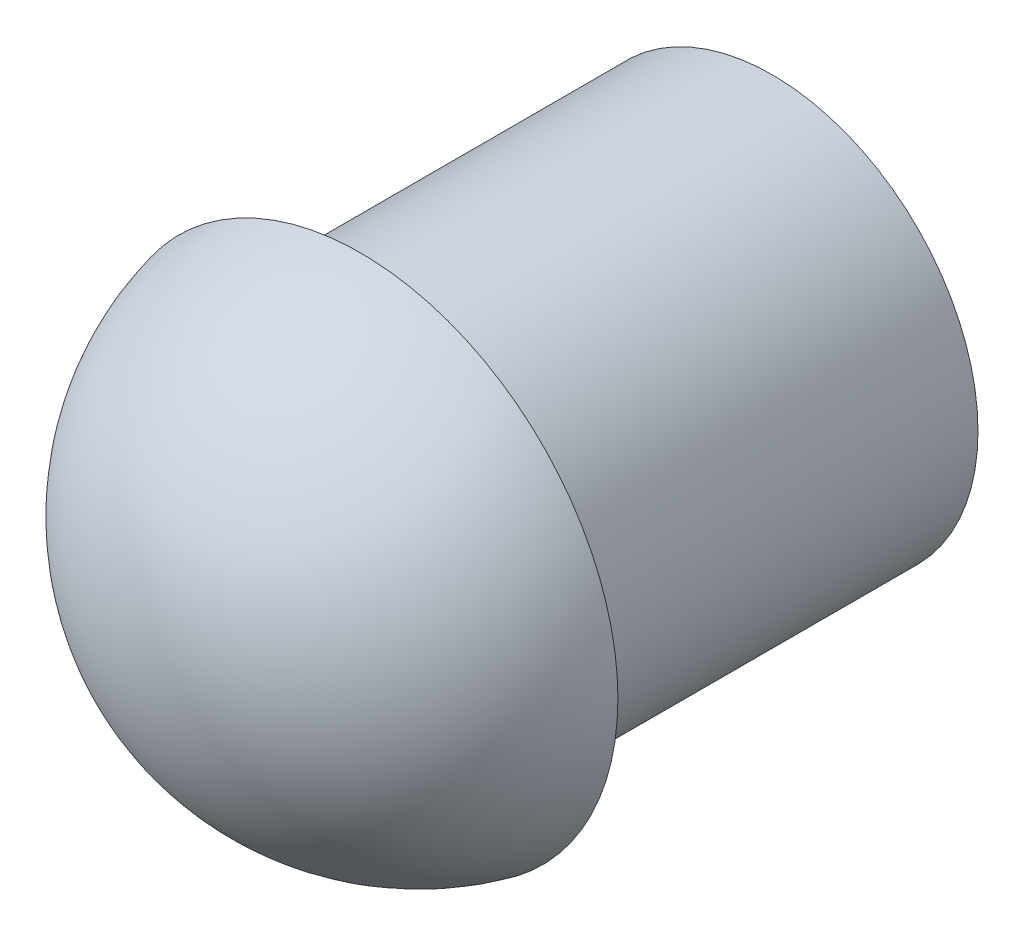
SolidWorks part; units mm, degrees
ref_plane "Front Plane" through (0, 0, 0) normal (0, 0, 1) x (1, 0, 0)
ref_plane "Top Plane" through (0, 0, 0) normal (0, 1, 0) x (1, 0, 0)
ref_plane "Right Plane" through (0, 0, 0) normal (1, 0, 0) x (0, 0, -1)
sketch "Sketch1" plane through (0, 0, 0) normal (0, 0, 1) x (1, 0, 0)
  circle A0 centre (0, 0) radius 20
  dimension "D1" = 40
extrude "Boss-Extrude1" add sketch "Sketch1" along normal blind 40
sketch "Sketch2" plane through (0, 0, 40) normal (0, 0, 1) x (1, 0, 0)
  circle A0 centre (0, 0) radius 25
  dimension "D1" = 50
extrude "Boss-Extrude2" add sketch "Sketch2" along normal blind 20
sketch "Sketch4" plane through (0, 0, 0) normal (0, 1, 0) x (1, 0, 0)
  line L0 (0, 11.2577) -> (0, -65.5795) construction
  line L1 (-25, -60) -> (25, -60) construction
  line L2 (25, -40) -> (27.0916, -40)
  line L3 (27.0916, -40) -> (27.0916, -68.7897)
  line L4 (27.0916, -68.7897) -> (0, -68.7897)
  line L5 (0, -68.7897) -> (0, -60)
  arc A0 (25, -40) -> (0, -60) centre (-0.0346, -34.3317) cw
revolve "Cut-Revolve5" cut sketch "Sketch4" angle 360 about L0
